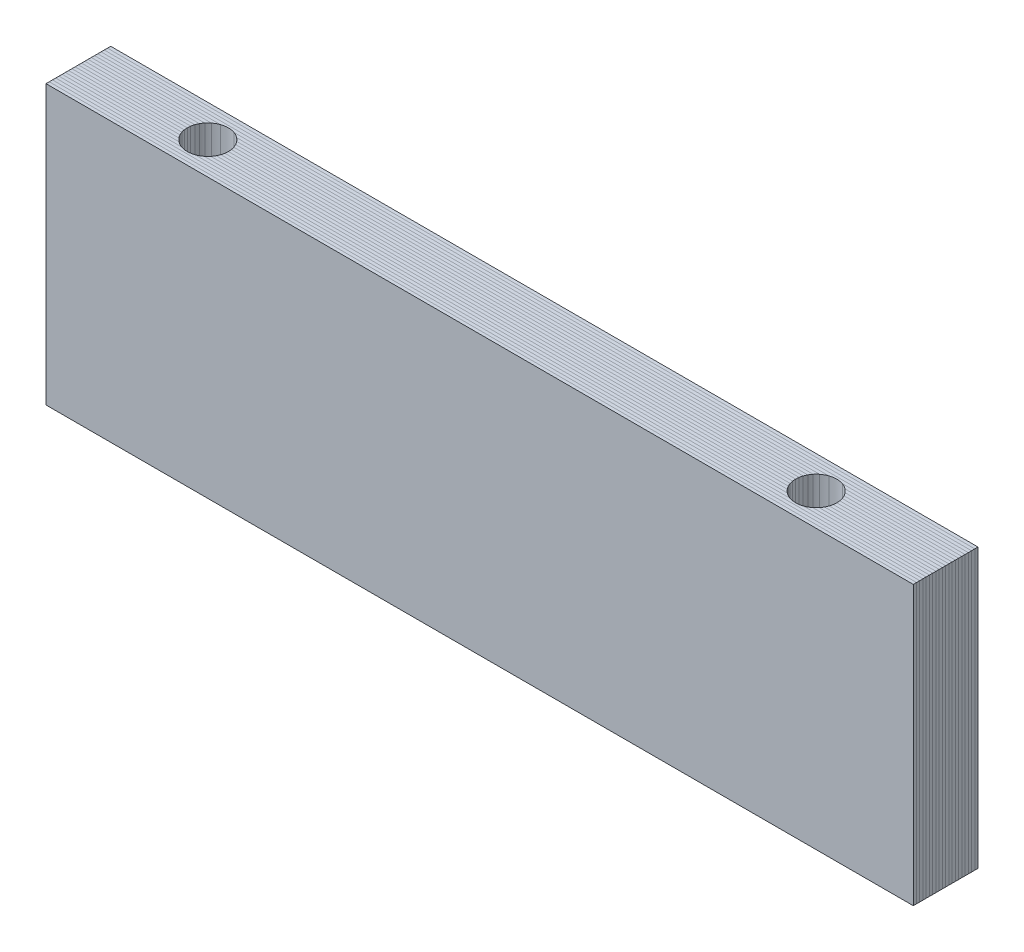
SolidWorks part; units mm, degrees
material "AISI 304"
ref_plane "Plano frontal" through (0, 0, 0) normal (0, 0, 1) x (1, 0, 0)
ref_plane "Plano superior" through (0, 0, 0) normal (0, 1, 0) x (1, 0, 0)
ref_plane "Plano direito" through (0, 0, 0) normal (1, 0, 0) x (0, 0, -1)
sketch "Esboço1" plane through (0, 0, 0) normal (0, 0, 1) x (1, 0, 0)
  line L1 (0, 0) -> (-134, 0)
  line L2 (0, 0) -> (0, 43)
  line L3 (0, 43) -> (-134, 43)
  line L4 (-134, 0) -> (-134, 43)
  dimension "D1" = 43
  dimension "D2" = 134
extrude "Ressalto-extrusão1" add sketch "Esboço1" along normal blind 0.5
sketch "Esboço2" plane through (0, 0, 0.5) normal (0, 0, 1) x (1, 0, 0)
  line L1 (-134, 43) -> (0, 43)
  line L2 (-134, 43) -> (-134, 0)
  line L3 (-134, 0) -> (0, 0)
  line L4 (0, 43) -> (0, 0)
extrude "Ressalto-extrusão3" add sketch "Esboço2" along normal blind 0.5 separate body
sketch "Esboço4" plane through (0, 0, 1) normal (0, 0, 1) x (1, 0, 0)
  line L1 (-134, 43) -> (0, 43)
  line L2 (-134, 43) -> (-134, 0)
  line L3 (-134, 0) -> (0, 0)
  line L4 (0, 43) -> (0, 0)
extrude "Ressalto-extrusão4" add sketch "Esboço4" along normal blind 0.5 separate body
sketch "Esboço5" plane through (0, 0, 1.5) normal (0, 0, 1) x (1, 0, 0)
  line L1 (-134, 43) -> (0, 43)
  line L2 (-134, 43) -> (-134, 0)
  line L3 (-134, 0) -> (0, 0)
  line L4 (0, 43) -> (0, 0)
extrude "Ressalto-extrusão5" add sketch "Esboço5" along normal blind 0.5 separate body
sketch "Esboço6" plane through (0, 0, 2) normal (0, 0, 1) x (1, 0, 0)
  line L1 (-134, 43) -> (0, 43)
  line L2 (-134, 43) -> (-134, 0)
  line L3 (-134, 0) -> (0, 0)
  line L4 (0, 43) -> (0, 0)
extrude "Ressalto-extrusão6" add sketch "Esboço6" along normal blind 0.5 separate body
sketch "Esboço7" plane through (0, 0, 2.5) normal (0, 0, 1) x (1, 0, 0)
  line L1 (-134, 43) -> (0, 43)
  line L2 (-134, 43) -> (-134, 0)
  line L3 (-134, 0) -> (0, 0)
  line L4 (0, 43) -> (0, 0)
extrude "Ressalto-extrusão7" add sketch "Esboço7" along normal blind 0.5 separate body
sketch "Esboço8" plane through (0, 0, 3) normal (0, 0, 1) x (1, 0, 0)
  line L1 (-134, 43) -> (0, 43)
  line L2 (-134, 43) -> (-134, 0)
  line L3 (-134, 0) -> (0, 0)
  line L4 (0, 43) -> (0, 0)
extrude "Ressalto-extrusão8" add sketch "Esboço8" along normal blind 0.5 separate body
sketch "Esboço9" plane through (0, 0, 3.5) normal (0, 0, 1) x (1, 0, 0)
  line L1 (-134, 43) -> (0, 43)
  line L2 (-134, 43) -> (-134, 0)
  line L3 (-134, 0) -> (0, 0)
  line L4 (0, 43) -> (0, 0)
extrude "Ressalto-extrusão9" add sketch "Esboço9" along normal blind 0.5 separate body
sketch "Esboço10" plane through (0, 0, 4) normal (0, 0, 1) x (1, 0, 0)
  line L1 (-134, 43) -> (0, 43)
  line L2 (-134, 43) -> (-134, 0)
  line L3 (-134, 0) -> (0, 0)
  line L4 (0, 43) -> (0, 0)
extrude "Ressalto-extrusão10" add sketch "Esboço10" along normal blind 0.5 separate body
sketch "Esboço11" plane through (0, 0, 4.5) normal (0, 0, 1) x (1, 0, 0)
  line L1 (-134, 43) -> (0, 43)
  line L2 (-134, 43) -> (-134, 0)
  line L3 (-134, 0) -> (0, 0)
  line L4 (0, 43) -> (0, 0)
extrude "Ressalto-extrusão11" add sketch "Esboço11" along normal blind 0.5 separate body
sketch "Esboço12" plane through (0, 0, 5) normal (0, 0, 1) x (1, 0, 0)
  line L1 (-134, 43) -> (0, 43)
  line L2 (-134, 43) -> (-134, 0)
  line L3 (-134, 0) -> (0, 0)
  line L4 (0, 43) -> (0, 0)
extrude "Ressalto-extrusão12" add sketch "Esboço12" along normal blind 0.5 separate body
sketch "Esboço13" plane through (0, 0, 5.5) normal (0, 0, 1) x (1, 0, 0)
  line L1 (-134, 43) -> (0, 43)
  line L2 (-134, 43) -> (-134, 0)
  line L3 (-134, 0) -> (0, 0)
  line L4 (0, 43) -> (0, 0)
extrude "Ressalto-extrusão13" add sketch "Esboço13" along normal blind 0.5 separate body
sketch "Esboço14" plane through (0, 0, 6) normal (0, 0, 1) x (1, 0, 0)
  line L1 (-134, 43) -> (0, 43)
  line L2 (-134, 43) -> (-134, 0)
  line L3 (-134, 0) -> (0, 0)
  line L4 (0, 43) -> (0, 0)
extrude "Ressalto-extrusão14" add sketch "Esboço14" along normal blind 0.5 separate body
sketch "Esboço15" plane through (0, 0, 6.5) normal (0, 0, 1) x (1, 0, 0)
  line L1 (-134, 43) -> (0, 43)
  line L2 (-134, 43) -> (-134, 0)
  line L3 (-134, 0) -> (0, 0)
  line L4 (0, 43) -> (0, 0)
extrude "Ressalto-extrusão15" add sketch "Esboço15" along normal blind 0.5 separate body
sketch "Esboço16" plane through (0, 0, 7) normal (0, 0, 1) x (1, 0, 0)
  line L1 (-134, 43) -> (0, 43)
  line L2 (-134, 43) -> (-134, 0)
  line L3 (-134, 0) -> (0, 0)
  line L4 (0, 43) -> (0, 0)
extrude "Ressalto-extrusão16" add sketch "Esboço16" along normal blind 0.5 separate body
sketch "Esboço17" plane through (0, 0, 7.5) normal (0, 0, 1) x (1, 0, 0)
  line L1 (-134, 43) -> (0, 43)
  line L2 (-134, 43) -> (-134, 0)
  line L3 (-134, 0) -> (0, 0)
  line L4 (0, 43) -> (0, 0)
extrude "Ressalto-extrusão17" add sketch "Esboço17" along normal blind 0.5 separate body
sketch "Esboço18" plane through (0, 0, 8) normal (0, 0, 1) x (1, 0, 0)
  line L1 (-134, 43) -> (0, 43)
  line L2 (-134, 43) -> (-134, 0)
  line L3 (-134, 0) -> (0, 0)
  line L4 (0, 43) -> (0, 0)
extrude "Ressalto-extrusão18" add sketch "Esboço18" along normal blind 0.5 separate body
sketch "Esboço19" plane through (0, 0, 8.5) normal (0, 0, 1) x (1, 0, 0)
  line L1 (-134, 43) -> (0, 43)
  line L2 (-134, 43) -> (-134, 0)
  line L3 (-134, 0) -> (0, 0)
  line L4 (0, 43) -> (0, 0)
extrude "Ressalto-extrusão19" add sketch "Esboço19" along normal blind 0.5 separate body
sketch "Esboço20" plane through (0, 0, 9) normal (0, 0, 1) x (1, 0, 0)
  line L1 (-134, 43) -> (0, 43)
  line L2 (-134, 43) -> (-134, 0)
  line L3 (-134, 0) -> (0, 0)
  line L4 (0, 43) -> (0, 0)
extrude "Ressalto-extrusão20" add sketch "Esboço20" along normal blind 0.5 separate body
sketch "Esboço21" plane through (0, 0, 9.5) normal (0, 0, 1) x (1, 0, 0)
  line L1 (-134, 43) -> (0, 43)
  line L2 (-134, 43) -> (-134, 0)
  line L3 (-134, 0) -> (0, 0)
  line L4 (0, 43) -> (0, 0)
extrude "Ressalto-extrusão21" add sketch "Esboço21" along normal blind 0.5 separate body
hole_wizard "Broca de rosquear para tarraxa de M3x0.51" positions "Esboço23" profile "Esboço24" hole size "M3x0.5" standard "Ansi Metric"
sketch "Esboço23" plane through (0, 43, 0) normal (0, 1, 0) x (1, 0, 0)
  line L0 (0, -5) -> (-134, -5) construction
  line L1 (0, -10) -> (-134, -10) construction
  line L2 (-134, -3) -> (-134, -2.5) construction
  line L3 (0, -5) -> (-134, -5) construction
  line L4 (0, -2) -> (0, -1.5) construction
  point P0 (-114, -5)
  point P2 (-20, -5)
  point P7 (0, 0)
  point P12 (-94.6272, -5)
  dimension "D1" = 5
  dimension "D2" = 20
  dimension "D3" = 20
  dimension "D4" = 5
sketch "Esboço24" plane through (-114, 43, 5) normal (1, 0, 0) x (0, 0, 1)
  line L0 (0, 0) -> (0, 23.49)
  line L1 (0, 23.49) -> (3.175, 21.5823)
  line L2 (3.175, 21.5823) -> (3.175, 0)
  line L5 (3.175, 0) -> (0, 0)
  line L10 (0, 23.49) -> (-3.175, 21.5823) construction
  line L11 (0, -6.35) -> (0, 107.95) construction
  dimension "Hole Dia." = 6.35
  dimension "Hole Depth" = 23.49
  dimension "Drill Angle" = 118
